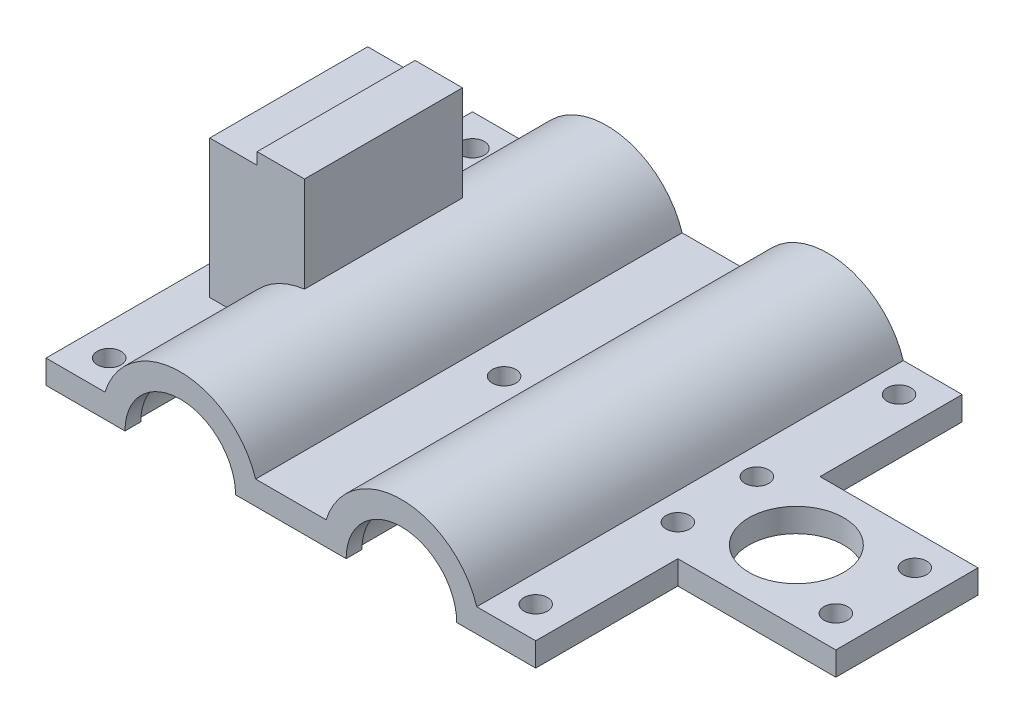
SolidWorks part; units mm, degrees
ref_plane "Front Plane" through (0, 0, 0) normal (0, 0, 1) x (1, 0, 0)
ref_plane "Top Plane" through (0, 0, 0) normal (0, 1, 0) x (1, 0, 0)
ref_plane "Right Plane" through (0, 0, 0) normal (1, 0, 0) x (0, 0, -1)
sketch "Sketch1" plane through (0, 0, 0) normal (0, 0, 1) x (1, 0, 0)
  line L0 (-31, 3) -> (-23.5394, 3)
  line L1 (-31, 0) -> (-21.5, 0)
  line L2 (-31, 0) -> (-31, 3)
  line L3 (-6.5, 0) -> (6.5, 0)
  line L4 (31, 0) -> (31, 3)
  line L5 (-4.4606, 3) -> (4.4606, 3)
  line L6 (23.5394, 3) -> (31, 3)
  line L7 (21.5, 0) -> (31, 0)
  arc A0 (-6.5, 0) -> (-21.5, 0) centre (-14, 0) ccw
  arc A1 (21.5, 0) -> (6.5, 0) centre (14, 0) ccw
  arc A2 (-4.4606, 3) -> (-23.5394, 3) centre (-14, 0) ccw
  arc A3 (23.5394, 3) -> (4.4606, 3) centre (14, 0) ccw
  dimension "D1" = 15
  dimension "D5" = 20
  dimension "D2" = 14
  dimension "D3" = 28
  dimension "D4" = 62
  dimension "D6" = 3
  dimension "D7" = 31
extrude "Boss-Extrude1" add sketch "Sketch1" along normal mid plane 54
sketch "Sketch2" plane through (0, 0, 27) normal (0, 0, 1) x (1, 0, 0)
  line L0 (-22, 0) -> (-21, 0)
  line L1 (-7, 0) -> (-6, 0)
  line L2 (21, 0) -> (22, 0)
  line L3 (6, 0) -> (7, 0)
  arc A0 (-6, 0) -> (-22, 0) centre (-14, 0) ccw
  arc A1 (-7, 0) -> (-21, 0) centre (-14, 0) ccw
  arc A2 (22, 0) -> (6, 0) centre (14, 0) ccw
  arc A3 (21, 0) -> (7, 0) centre (14, 0) ccw
  dimension "D1" = 16
  dimension "D2" = 16
  dimension "D3" = 14
extrude "Boss-Extrude2" add sketch "Sketch2" against normal blind 2
mirror "Mirror1" about plane through (0, 0, 0) normal (0, 0, 1) of "Boss-Extrude2"
sketch "Sketch3" plane through (0, 0, 0) normal (0, 0, 1) x (1, 0, 0)
  line L0 (-22, 0) -> (-21, 0)
  line L1 (6, 0) -> (7, 0)
  line L2 (-7, 0) -> (-6, 0)
  line L3 (21, 0) -> (22, 0)
  arc A0 (-6, 0) -> (-22, 0) centre (-14, 0) ccw
  arc A1 (-7, 0) -> (-21, 0) centre (-14, 0) ccw
  arc A2 (21, 0) -> (7, 0) centre (14, 0) ccw
  arc A3 (22, 0) -> (6, 0) centre (14, 0) ccw
  dimension "D1" = 16
  dimension "D2" = 14
extrude "Boss-Extrude3" add sketch "Sketch3" along normal mid plane 2
sketch "Sketch4" plane through (0, 3, 0) normal (0, 1, 0) x (1, 0, 0)
  line L0 (-23.5394, -27) -> (-31, -27) construction
  line L1 (-31, -27) -> (-31, 27) construction
  line L2 (-23.5394, 27) -> (-31, 27) construction
  line L3 (31, 27) -> (23.5394, 27) construction
  line L4 (31, -27) -> (31, 27) construction
  line L5 (31, -27) -> (23.5394, -27) construction
  circle A0 centre (-27, 23) radius 1.5
  circle A1 centre (-27, -23) radius 1.5
  circle A2 centre (27, -23) radius 1.5
  circle A3 centre (27, 23) radius 1.5
  circle A4 centre (0, 0) radius 1.5
  dimension "D1" = 3
  dimension "D2" = 4
  dimension "D3" = 4
  dimension "D4" = 4
  dimension "D5" = 4
  dimension "D6" = 4
  dimension "D7" = 4
  dimension "D8" = 4
  dimension "D9" = 4
extrude "Cut-Extrude1" cut sketch "Sketch4" against normal through all
sketch "Sketch5" plane through (0, 3, 0) normal (0, 1, 0) x (1, 0, 0)
  line L0 (23.5394, 9) -> (51, 9)
  line L1 (23.5394, -27) -> (23.5394, 27) construction
  line L2 (51, 9) -> (51, -9)
  line L3 (51, -9) -> (23.5394, -9)
  line L4 (23.5394, -9) -> (23.5394, 9)
  dimension "D1" = 51
  dimension "D7" = 9
  dimension "D8" = 18
extrude "Boss-Extrude4" add sketch "Sketch5" against normal blind 3
sketch "Sketch6" plane through (0, 3, 0) normal (0, 1, 0) x (1, 0, 0)
  line L1 (31, -27) -> (31, -9) construction
  circle A0 centre (47, 5) radius 1.5
  circle A1 centre (47, -5) radius 1.5
  circle A2 centre (27, -5) radius 1.5
  circle A3 centre (27, 5) radius 1.5
  circle A4 centre (37, 0) radius 6
  dimension "D1" = 3
  dimension "D2" = 12
  dimension "D3" = 10
  dimension "D4" = 10
  dimension "D5" = 20
  dimension "D6" = 5
  dimension "D7" = 4
  dimension "D8" = 5
extrude "Cut-Extrude2" cut sketch "Sketch6" against normal through all
sketch "Sketch7" plane through (0, 0, 0) normal (0, 0, 1) x (1, 0, 0)
  line L0 (-27.2697, 3) -> (-23.5394, 3)
  line L1 (-27.2697, 3) -> (-27.2697, 20.5)
  line L2 (-27.2697, 20.5) -> (-15.2697, 20.5)
  line L3 (-15.2697, 20.5) -> (-15.2697, 9.9191)
  arc A0 (-15.2697, 9.9191) -> (-23.5394, 3) centre (-14, 0) ccw
  arc A1 (-4.4606, 3) -> (-23.5394, 3) centre (-14, 0) ccw construction
  dimension "D1" = 12
  dimension "D2" = 17.5
extrude "Boss-Extrude5" add sketch "Sketch7" along normal mid plane 20
sketch "Sketch8" plane through (0, 0, -10) normal (0, 0, -1) x (-1, 0, 0)
  line L0 (21.2697, 20.5) -> (21.2697, 22)
  line L2 (15.2697, 20.5) -> (27.2697, 20.5) construction
  line L3 (21.2697, 22) -> (15.2697, 22)
  line L4 (15.2697, 22) -> (15.2697, 20.5)
  line L5 (27.2697, 20.5) -> (27.2697, 3) construction
  line L6 (21.2697, 20.5) -> (15.2697, 20.5)
  dimension "D1" = 1.5
  dimension "D2" = 6
extrude "Boss-Extrude6" add sketch "Sketch8" against normal blind 20 contours L0 L3 L4 L6
